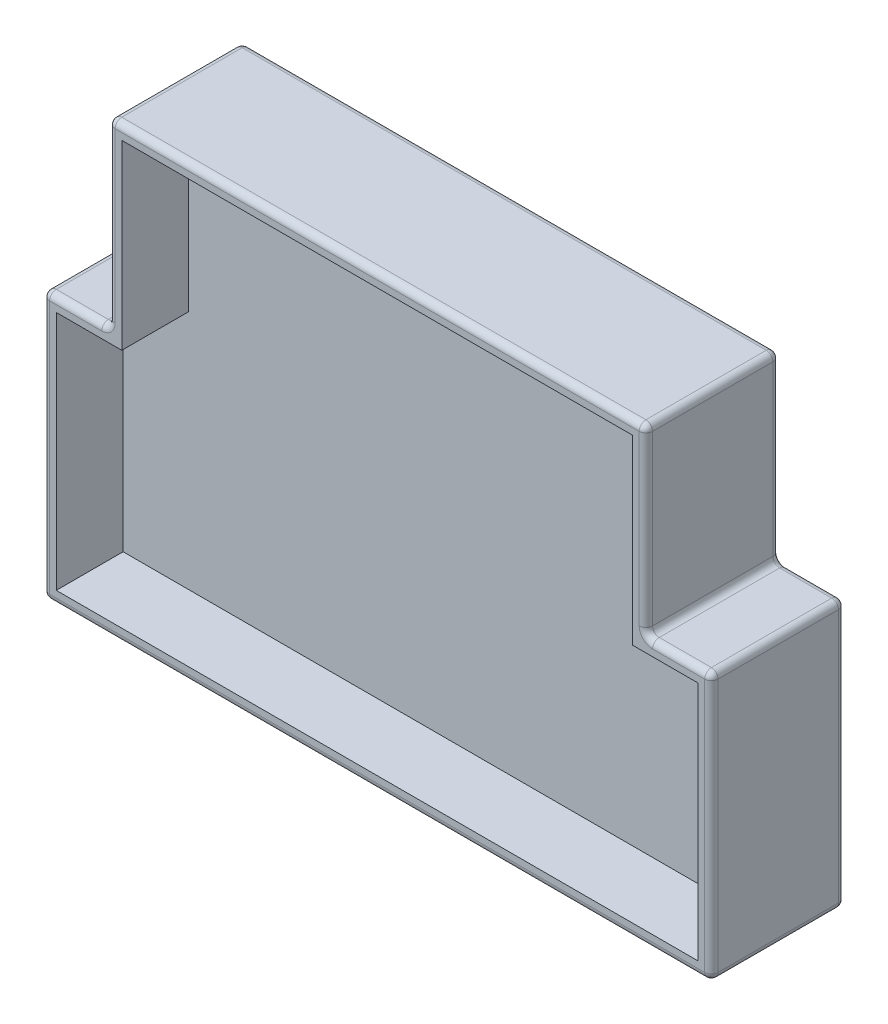
SolidWorks part; units mm, degrees
ref_plane "Спереди" through (0, 0, 0) normal (0, 0, 1) x (1, 0, 0)
ref_plane "Сверху" through (0, 0, 0) normal (0, 1, 0) x (1, 0, 0)
ref_plane "Справа" through (0, 0, 0) normal (1, 0, 0) x (0, 0, -1)
sketch "Эскиз1" plane through (0, 0, 0) normal (0, 0, 1) x (1, 0, 0)
  line L1 (50, -20) -> (-50, -20)
  line L2 (50, -20) -> (50, 20)
  line L3 (50, 20) -> (-50, 20)
  line L4 (-50, -20) -> (-50, 20)
  line L5 (50, -20) -> (-50, 20) construction
  line L6 (50, 20) -> (-50, -20) construction
  point P0 (0, 0)
  dimension "D1" = 100
  dimension "D2" = 40
extrude "Бобышка-Вытянуть1" add sketch "Эскиз1" along normal blind 20
sketch "Эскиз2" plane through (0, 0, 20) normal (0, 0, 1) x (1, 0, 0)
  line L1 (48, -18) -> (-48, -18)
  line L2 (48, -18) -> (48, 18)
  line L3 (48, 18) -> (-48, 18)
  line L4 (-48, -18) -> (-48, 18)
  line L5 (48, -18) -> (-48, 18) construction
  line L6 (48, 18) -> (-48, -18) construction
  point P0 (0, 0)
  dimension "D1" = 36
  dimension "D2" = 96
extrude "Вырез-Вытянуть1" cut sketch "Эскиз2" against normal blind 10
sketch "Эскиз3" plane through (0, 20, 0) normal (0, 1, 0) x (1, 0, 0)
  line L1 (50, -20) -> (-50, -20) construction
  line L3 (50, 0) -> (-50, 0) construction
  line L4 (-40.2, 0) -> (-40.2, -20)
  line L5 (-40.2, -20) -> (40.2, -20)
  line L6 (40.2, -20) -> (40.2, 0)
  line L7 (40.2, 0) -> (-40.2, 0)
  point P0 (0, 0)
  dimension "D1" = 40.2
extrude "Бобышка-Вытянуть2" add sketch "Эскиз3" along normal blind 27.2
sketch "Эскиз4" plane through (0, 18, 0) normal (0, -1, 0) x (1, 0, 0)
  line L0 (0, 20) -> (0, 10) construction
  line L1 (48, 20) -> (-48, 20) construction
  line L2 (48, 10) -> (-48, 10) construction
  line L3 (-38.2, 20) -> (0, 20)
  line L4 (0, 20) -> (38.2, 20)
  line L5 (38.2, 20) -> (38.2, 10)
  line L6 (38.2, 10) -> (-38.2, 10)
  line L7 (-38.2, 10) -> (-38.2, 20)
  dimension "D1" = 38.2
  dimension "D2" = 38.2
extrude "Вырез-Вытянуть2" cut sketch "Эскиз4" against normal blind 27.2
fillet "Скругление1" radius 1 24 edges at (50, 0, 20) (40.2, 33.6, 20) (0, -20, 20) (50, -20, 10) (50, 20, 10) (45.1, 20, 20) (40.2, 20, 10) (40.2, 47.2, 10) (0, 47.2, 20) (-40.2, 47.2, 10) (-40.2, 33.6, 20) (-45.1, 20, 20) (-40.2, 20, 10) (-50, 20, 10) (-50, 0, 20) (-50, -20, 10) (0, -20, 0) (50, 0, 0) (45.1, 20, 0) (40.2, 33.6, 0) (0, 47.2, 0) (-40.2, 33.6, 0) (-45.1, 20, 0) (-50, 0, 0)
